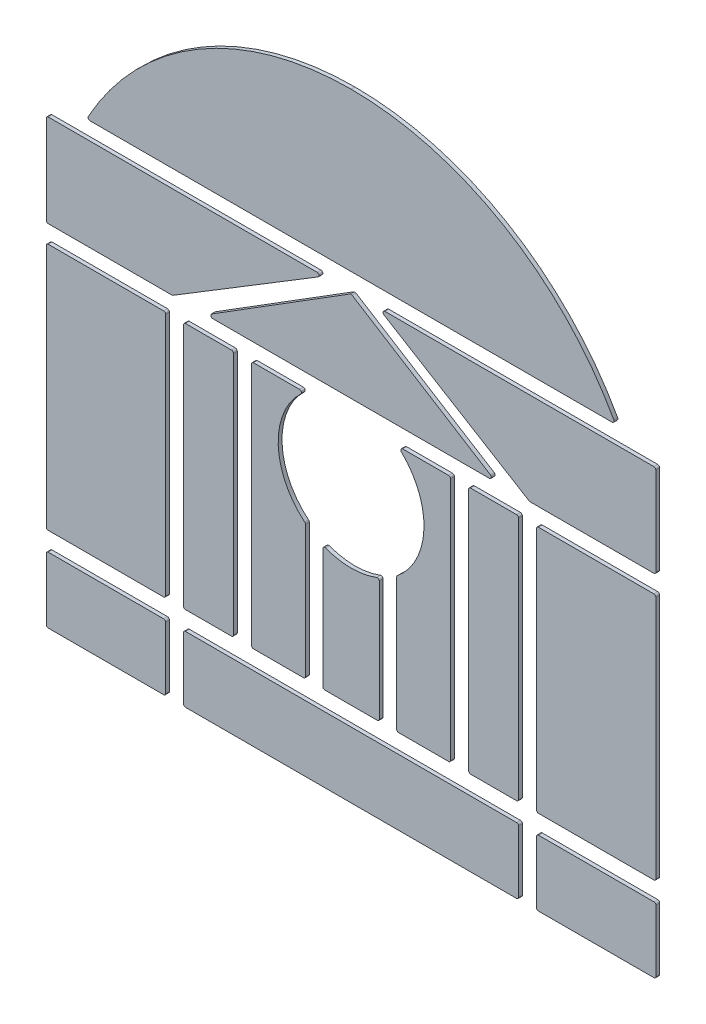
SolidWorks part; units mm, degrees
ref_plane "Front Plane" through (0, 0, 0) normal (0, 0, 1) x (1, 0, 0)
ref_plane "Top Plane" through (0, 0, 0) normal (0, 1, 0) x (1, 0, 0)
ref_plane "Right Plane" through (0, 0, 0) normal (1, 0, 0) x (0, 0, -1)
sketch "Sketch1" plane through (0, 0, 0) normal (0, 0, 1) x (1, 0, 0)
  line B0 (-0.012, 54.4476) -> (-98.7709, 54.4259)
  line B1 (-98.7709, 54.4259) -> (-98.7589, 0.0337)
  line B2 (-98.7589, 0.0337) -> (0, 0.0554)
  line B3 (0, 0.0554) -> (-0.012, 54.4476)
  line B4 (-390.788, 0) -> (-113.6255, 0.0305)
  line B5 (-113.6255, 0.0305) -> (-113.6375, 54.4226)
  line B6 (-113.6375, 54.4226) -> (-390.788, 54.3922)
  line B7 (-390.788, 54.3922) -> (-390.788, 0)
  line B8 (-504.4135, 54.3922) -> (-504.4135, 0)
  line B9 (-504.4135, 0) -> (-405.6546, 0)
  line B10 (-405.6546, 0) -> (-405.6546, 54.3922)
  line B11 (-405.6546, 54.3922) -> (-504.4135, 54.3922)
  line B12 (-504.4135, 275.0244) -> (-504.4135, 70.0243)
  line B13 (-504.4135, 70.0243) -> (-405.6546, 70.0243)
  line B14 (-405.6546, 70.0243) -> (-405.6546, 275.0244)
  line B15 (-405.6546, 275.0244) -> (-504.4135, 275.0244)
  line B16 (-390.788, 275.0244) -> (-390.788, 70.0243)
  line B17 (-390.788, 70.0243) -> (-349.5338, 70.0243)
  line B18 (-349.5338, 70.0243) -> (-349.5338, 275.0244)
  line B19 (-349.5338, 275.0244) -> (-390.788, 275.0244)
  line B20 (-290.7279, 275.0244) -> (-334.5576, 275.0244)
  line B21 (-334.5576, 275.0244) -> (-334.5576, 70.0243)
  line B22 (-334.5576, 70.0243) -> (-289.9539, 70.0243)
  line B23 (-289.9539, 70.0243) -> (-289.9539, 181.5441)
  line B24 (-275.5689, 172.9824) -> (-275.5689, 70.0243)
  line B25 (-275.5689, 70.0243) -> (-228.86, 70.0294)
  line B26 (-228.86, 70.0294) -> (-228.8826, 172.9665)
  line B27 (-214.4995, 181.5121) -> (-214.475, 70.0326)
  line B28 (-214.475, 70.0326) -> (-169.8713, 70.0424)
  line B29 (-169.8713, 70.0424) -> (-169.9164, 275.0425)
  line B30 (-169.9164, 275.0425) -> (-213.6958, 275.0329)
  line B31 (-113.686, 275.0549) -> (-154.9402, 275.0458)
  line B32 (-154.9402, 275.0458) -> (-154.8951, 70.0457)
  line B33 (-154.8951, 70.0457) -> (-113.6409, 70.0548)
  line B34 (-113.6409, 70.0548) -> (-113.686, 275.0549)
  line B35 (-0.0604, 275.0798) -> (-98.8194, 275.0581)
  line B36 (-98.8194, 275.0581) -> (-98.7743, 70.058)
  line B37 (-98.7743, 70.058) -> (-0.0154, 70.0797)
  line B38 (-0.0154, 70.0797) -> (-0.0604, 275.0798)
  line B39 (-229.8564, 366.2091) -> (-104.4817, 289.8032)
  line B40 (-104.4817, 289.8032) -> (-0.0637, 289.8262)
  line B41 (-0.0637, 289.8262) -> (-0.0805, 366.2596)
  line B42 (-0.0805, 366.2596) -> (-229.8564, 366.2091)
  line B43 (-372.2423, 289.7707) -> (-132.2349, 289.7971)
  line B44 (-132.2349, 289.7971) -> (-252.2469, 364.7566)
  line B45 (-252.2469, 364.7566) -> (-372.2423, 289.7707)
  line B46 (-274.6376, 366.2041) -> (-504.4135, 366.2041)
  line B47 (-504.4135, 366.2041) -> (-504.4135, 289.7707)
  line B48 (-504.4135, 289.7707) -> (-399.9955, 289.7707)
  line B49 (-399.9955, 289.7707) -> (-274.6376, 366.2041)
  line B50 (-470.9648, 380.7452) -> (-33.5324, 380.7933)
  arc B51 (-290.7279, 275.0244) -> (-289.9539, 181.5441) centre (-252.2068, 228.6) ccw
  arc B52 (-275.5689, 172.9824) -> (-228.8826, 172.9665) centre (-252.2068, 228.6) ccw
  arc B53 (-214.4995, 181.5121) -> (-213.6958, 275.0329) centre (-252.2068, 228.6) ccw
  arc B54 (-252.263, 511.4378) -> (-470.9648, 380.7452) centre (-252.263, 263.1029) ccw
  arc B55 (-33.5324, 380.7933) -> (-252.263, 511.4378) centre (-252.2084, 263.1029) ccw
sketch_block_instance "Block1-1"
sketch_block "Block1"
extrude "Boss-Extrude1" add sketch "Sketch1" along normal blind 3.175 contours B10 B11 B8 B9 | B14 B15 B12 B13 | B48 B49 B46 B47 | B50 B55 B54 | B41 B42 B39 B40 | B44 B45 B43 | B37 B38 B35 B36 | B2 B3 B0 B1 | B6 B7 B4 B5 | B33 B34 B31 B32 | B53 B27 B28 B29 B30 | B52 B24 B25 B26 | B51 B20 B21 B22 B23 | B18 B19 B16 B17
fillet "Fillet1" radius 1.59 2 edges at (-33.5324, 380.7933, 1.5875) (-470.9648, 380.7452, 1.5875)
fillet "Fillet2" radius 1.59 4 edges at (-229.8564, 366.2091, 1.5875) (-104.4817, 289.8032, 1.5875) (-0.0805, 366.2596, 1.5875) (-0.0637, 289.8262, 1.5875)
fillet "Fillet3" radius 1.59 3 edges at (-372.2423, 289.7707, 1.5875) (-252.2469, 364.7566, 1.5875) (-132.2349, 289.7971, 1.5875)
fillet "Fillet4" radius 1.59 4 edges at (-399.9955, 289.7707, 1.5875) (-504.4135, 289.7707, 1.5875) (-504.4135, 366.2041, 1.5875) (-274.6376, 366.2041, 1.5875)
fillet "Fillet5" radius 1.59 4 edges at (-504.4135, 275.0244, 1.5875) (-405.6546, 275.0244, 1.5875) (-405.6546, 70.0243, 1.5875) (-504.4135, 70.0243, 1.5875)
fillet "Fillet6" radius 1.59 4 edges at (-405.6546, 0, 1.5875) (-504.4135, 0, 1.5875) (-504.4135, 54.3922, 1.5875) (-405.6546, 54.3922, 1.5875)
fillet "Fillet7" radius 1.59 4 edges at (-113.6375, 54.4226, 1.5875) (-113.6255, 0.0305, 1.5875) (-390.788, 54.3922, 1.5875) (-390.788, 0, 1.5875)
fillet "Fillet8" radius 1.59 4 edges at (-98.7709, 54.4259, 1.5875) (-0.012, 54.4476, 1.5875) (0, 0.0554, 1.5875) (-98.7589, 0.0337, 1.5875)
fillet "Fillet9" radius 1.59 4 edges at (-98.8194, 275.0581, 1.5875) (-0.0604, 275.0798, 1.5875) (-98.7743, 70.058, 1.5875) (-0.0154, 70.0797, 1.5875)
fillet "Fillet10" radius 1.59 4 edges at (-154.8951, 70.0457, 1.5875) (-113.6409, 70.0548, 1.5875) (-154.9402, 275.0458, 1.5875) (-113.686, 275.0549, 1.5875)
fillet "Fillet11" radius 1.59 5 edges at (-214.4995, 181.5121, 1.5875) (-214.475, 70.0326, 1.5875) (-169.9164, 275.0425, 1.5875) (-213.6958, 275.0329, 1.5875) (-169.8713, 70.0424, 1.5875)
fillet "Fillet12" radius 1.59 4 edges at (-275.5689, 172.9824, 1.5875) (-228.8826, 172.9665, 1.5875) (-275.5689, 70.0243, 1.5875) (-228.86, 70.0294, 1.5875)
fillet "Fillet13" radius 1.59 5 edges at (-290.7279, 275.0244, 1.5875) (-334.5576, 275.0244, 1.5875) (-334.5576, 70.0243, 1.5875) (-289.9539, 70.0243, 1.5875) (-289.9539, 181.5441, 1.5875)
fillet "Fillet14" radius 1.59 4 edges at (-349.5338, 70.0243, 1.5875) (-390.788, 70.0243, 1.5875) (-349.5338, 275.0244, 1.5875) (-390.788, 275.0244, 1.5875)
